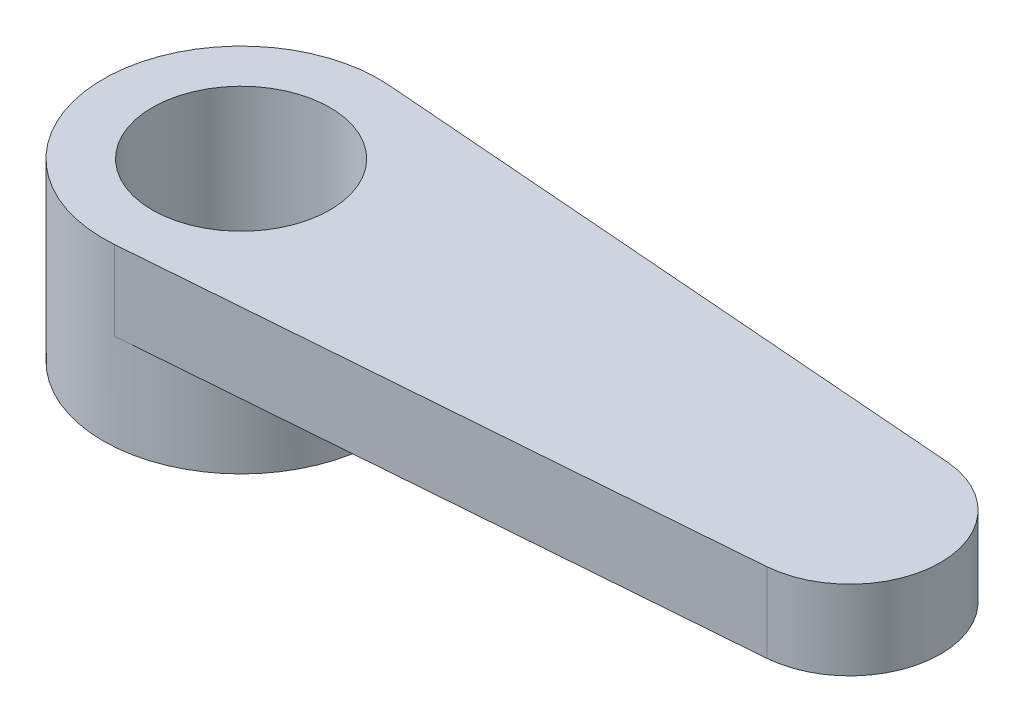
SolidWorks part; units mm, degrees
ref_plane "Front Plane" through (0, 0, 0) normal (0, 0, 1) x (1, 0, 0)
ref_plane "Top Plane" through (0, 0, 0) normal (0, 1, 0) x (1, 0, 0)
ref_plane "Right Plane" through (0, 0, 0) normal (1, 0, 0) x (0, 0, -1)
sketch "Sketch1" plane through (0, 0, 0) normal (0, 1, 0) x (1, 0, 0)
  circle A0 centre (0, 0) radius 3.65
  circle A1 centre (0, 0) radius 2.35
  dimension "D1" = 7.3
  dimension "D2" = 4.7
extrude "Boss-Extrude1" add sketch "Sketch1" along normal blind 4.64
sketch "Sketch2" plane through (0, 4.64, 0) normal (0, 1, 0) x (1, 0, 0)
  line L0 (0, 0) -> (16.1, 0) construction
  line L1 (0.2834, 3.639) -> (16.3037, 2.3914)
  line L2 (0.2834, -3.639) -> (16.3037, -2.3914)
  arc A0 (0.2834, -3.639) -> (0.2834, 3.639) centre (0, 0) ccw
  arc A1 (16.3037, -2.3914) -> (16.3037, 2.3914) centre (16.1, 0) ccw
  dimension "D1" = 16.1
  dimension "D2" = 7.3
  dimension "D3" = 2.4
extrude "Boss-Extrude2" add sketch "Sketch2" against normal blind 2.1
